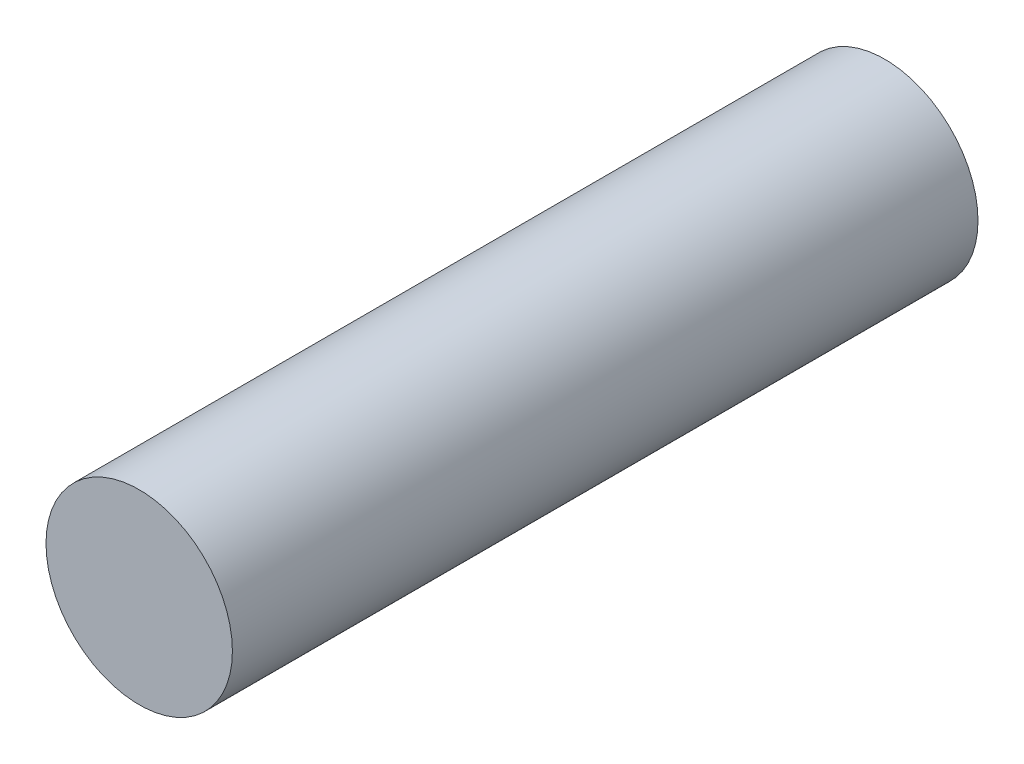
SolidWorks part; units mm, degrees
ref_plane "Front Plane" through (0, 0, 0) normal (1, 0, 0) x (0, 1, 0)
ref_plane "Top Plane" through (0, 0, 0) normal (0, 0, 1) x (0, 1, 0)
ref_plane "Right Plane" through (0, 0, 0) normal (0, 1, 0) x (-1, 0, 0)
sketch "Sketch1" plane through (0, 0, 0) normal (0, 0, 1) x (0, 1, 0)
  circle A0 centre (0, 0) radius 3.175
  dimension "D1" = 6.35
extrude "Boss-Extrude1" add sketch "Sketch1" along normal blind 25.4
equation "\"OUT_SHAFT_DIA\"=0.25"
equation "\"SHAFT_LENGTH\"= 1"
equation "\"D1@Sketch1\"=\"OUT_SHAFT_DIA\""
equation "\"LENGTH\"= 0.1'IGNORE"
equation "\"D1@Boss-Extrude1\"= \"SHAFT_LENGTH\""
